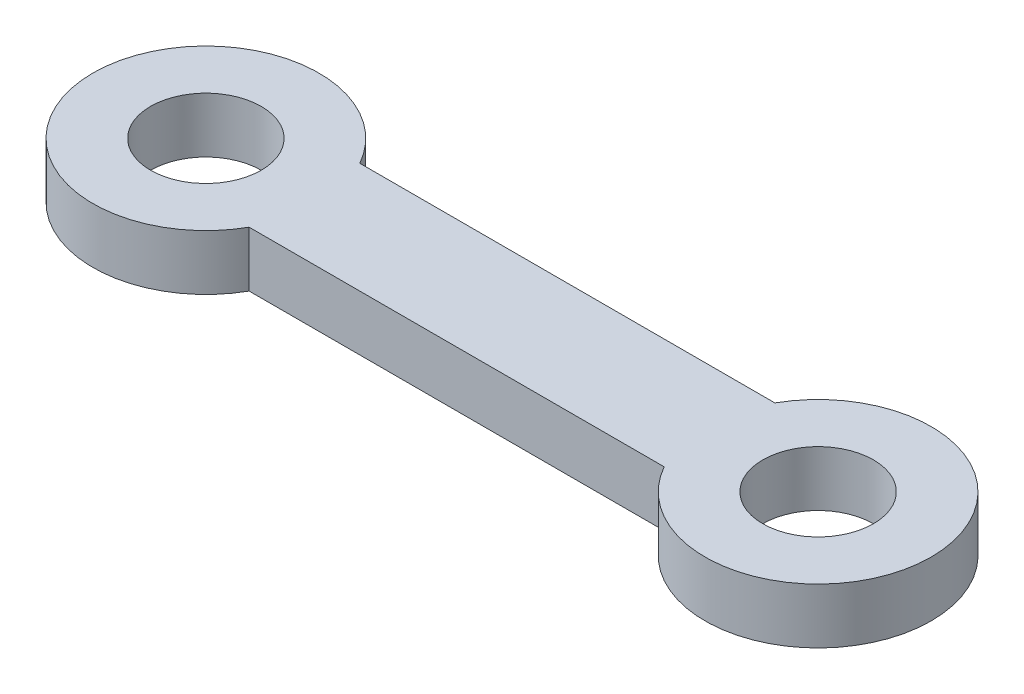
SolidWorks part; units mm, degrees
ref_plane "Front Plane" through (0, 0, 0) normal (0, 0, 1) x (1, 0, 0)
ref_plane "Top Plane" through (0, 0, 0) normal (0, 1, 0) x (1, 0, 0)
ref_plane "Right Plane" through (0, 0, 0) normal (1, 0, 0) x (0, 0, -1)
sketch "Sketch4" plane through (0, 0, 0) normal (0, 1, 0) x (1, 0, 0)
  line L0 (0, 0) -> (0, -116.8928) construction
  line L1 (-75, 20) -> (75, 20)
  line L2 (-75, 20) -> (-75, -20)
  line L3 (-75, -20) -> (75, -20)
  line L4 (75, 20) -> (75, -20)
  line L5 (-75, 20) -> (75, -20) construction
  line L6 (-75, -20) -> (75, 20) construction
  circle A1 centre (-110.6342, 0) radius 40.8631
  circle A2 centre (110.6342, 0) radius 40.8631
  point P0 (0, 0)
  point P12 (0, 0)
  point P13 (0, 0)
  point P14 (0, 0)
  dimension "D1" = 40
  dimension "D2" = 150
extrude "Boss-Extrude1" add sketch "Sketch4" along normal blind 20 contours L3 A2 L1 A1 | A2 L4 | A2 L4
sketch "Sketch6" plane through (0, 0, 0) normal (0, -1, 0) x (1, 0, 0)
  circle A0 centre (-110.6342, 0) radius 20
  circle A1 centre (110.6342, 0) radius 20
  point P0 (0, 0)
  dimension "D1" = 40
extrude "Cut-Extrude1" cut sketch "Sketch6" against normal up to next contours A1 | A0
